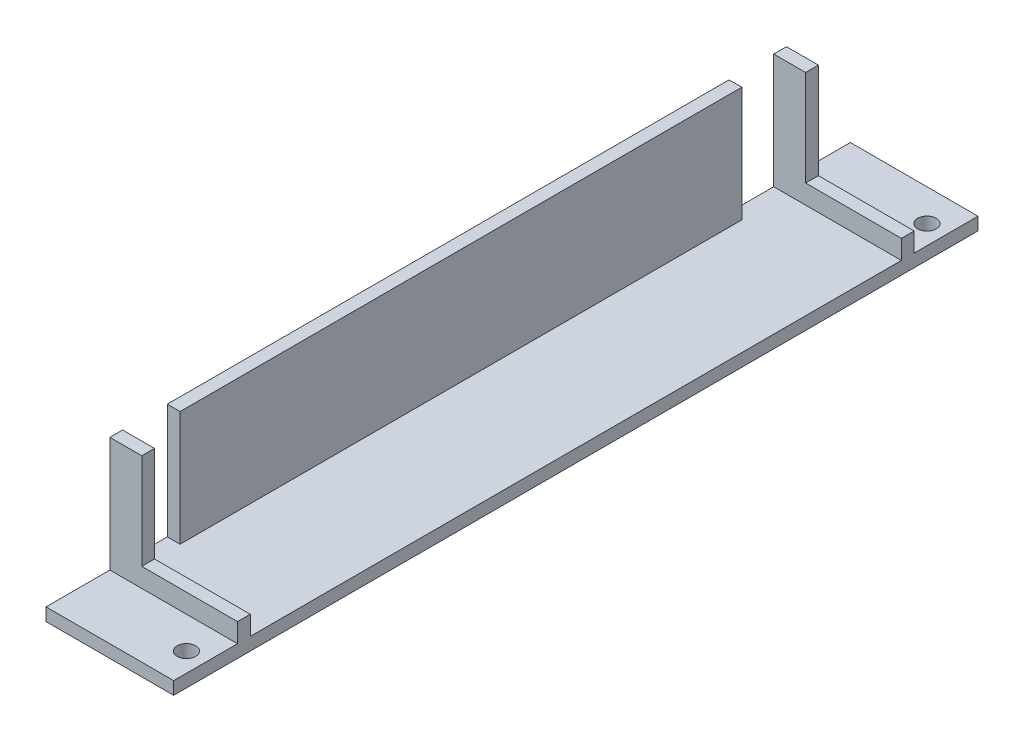
SolidWorks part; units mm, degrees
ref_plane "Front Plane" through (0, 0, 0) normal (0, 0, 1) x (1, 0, 0)
ref_plane "Top Plane" through (0, 0, 0) normal (0, 1, 0) x (1, 0, 0)
ref_plane "Right Plane" through (0, 0, 0) normal (1, 0, 0) x (0, 0, -1)
sketch "Sketch1" plane through (0, 0, 0) normal (0, 0, 1) x (1, 0, 0)
  line L0 (-10, 0) -> (10, 0)
  line L1 (-10, 0) -> (-10, 20)
  line L2 (-10, 20) -> (-8, 20)
  line L3 (-8, 20) -> (-8, 2)
  line L4 (-8, 2) -> (10, 2)
  line L5 (10, 2) -> (10, 0)
  point P4 (0, 0)
  dimension "D1" = 2
  dimension "D2" = 2
  dimension "D3" = 18
  dimension "D4" = 18
extrude "Boss-Extrude1" add sketch "Sketch1" along normal blind 126
sketch "Sketch2" plane through (-10, 0, 0) normal (-1, 0, 0) x (0, 0, 1)
  line L0 (126, 20) -> (0, 20) construction
  line L1 (12, 20) -> (19, 20)
  line L2 (12, 20) -> (12, 2)
  line L3 (12, 2) -> (19, 2)
  line L4 (19, 20) -> (19, 2)
  line L5 (126, 0) -> (0, 0) construction
  line L6 (107, 20) -> (114, 20)
  line L7 (107, 20) -> (107, 2)
  line L8 (107, 2) -> (114, 2)
  line L9 (114, 20) -> (114, 2)
  line L10 (126, 20) -> (126, 0) construction
  line L11 (10, 20) -> (0, 20)
  line L12 (10, 20) -> (10, 2)
  line L13 (10, 2) -> (0, 2)
  line L14 (0, 20) -> (0, 2)
  line L15 (116, 20) -> (126, 20)
  line L16 (116, 20) -> (116, 2)
  line L17 (116, 2) -> (126, 2)
  line L18 (126, 20) -> (126, 2)
  point P12 (63, 0)
  dimension "D1" = 2
  dimension "D2" = 2
  dimension "D3" = 88
  dimension "D4" = 7
  dimension "D5" = 7
  dimension "D6" = 44
  dimension "D7" = 2
  dimension "D8" = 2
extrude "Cut-Extrude1" cut sketch "Sketch2" against normal through all
sketch "Sketch3" plane through (0, 0, 116) normal (0, 0, 1) x (1, 0, 0)
  line L0 (10, 2) -> (-10, 2) construction
  line L1 (-10, 20) -> (-5, 20)
  line L2 (-10, 20) -> (-10, 2)
  line L3 (-10, 2) -> (-5, 2)
  line L4 (-5, 20) -> (-5, 5)
  line L5 (-5, 5) -> (10, 5)
  line L6 (10, 5) -> (10, 2)
  line L7 (10, 2) -> (-5, 2)
  dimension "D1" = 5
  dimension "D2" = 15
  dimension "D3" = 3
extrude "Boss-Extrude2" add sketch "Sketch3" against normal blind 2
ref_plane "Plane1" through (0, 0, 63) normal (0, 0, 1) x (1, 0, 0)
hole_wizard "M2.5 Clearance Hole1" positions "Sketch4" profile "Sketch5" hole size "M2.5" standard "ISO" end condition through all
sketch "Sketch4" plane through (0, 2, 0) normal (0, 1, 0) x (1, 0, 0)
  line L0 (10, -126) -> (10, -116) construction
  line L1 (10, -126) -> (-10, -126) construction
  point P0 (7, -121)
  dimension "D1" = 3
  dimension "D2" = 5
sketch "Sketch5" plane through (7, 2, 121) normal (1, 0, 0) x (0, 0, 1)
  line L0 (0, 0) -> (0, 2)
  line L1 (0, 2) -> (1.45, 2)
  line L2 (1.45, 2) -> (1.45, 0)
  line L5 (1.45, 0) -> (0, 0)
  line L11 (0, -6.35) -> (0, 107.95) construction
  dimension "Thru Hole Dia." = 2.9
  dimension "Thru Hole Depth" = 2
mirror "Mirror1" about plane through (0, 0, 63) normal (0, 0, 1) of "M2.5 Clearance Hole1", "Boss-Extrude2"
